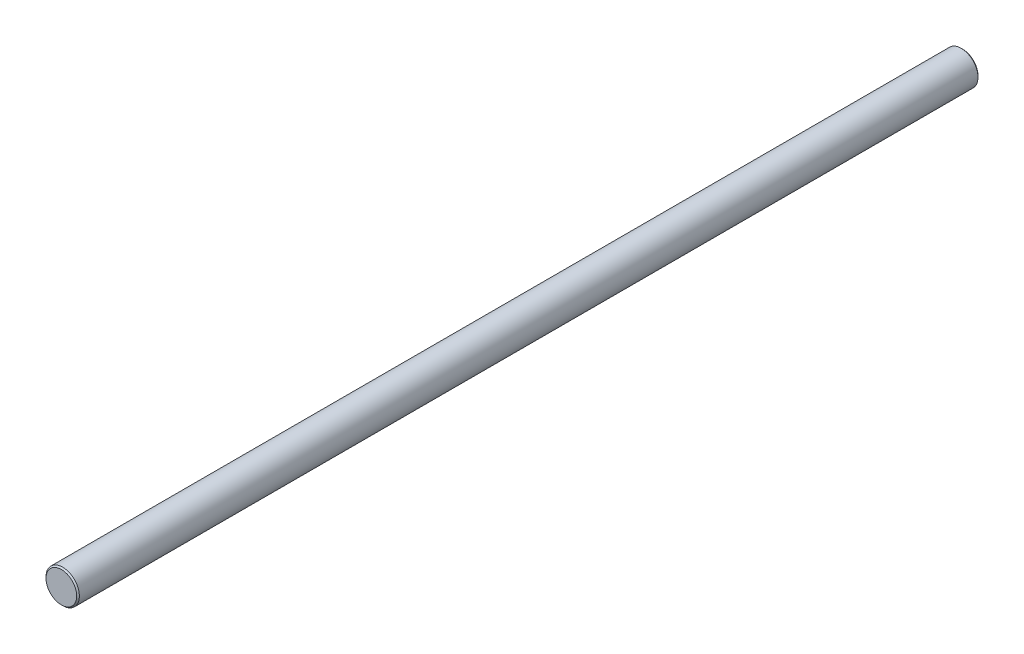
SolidWorks part; units mm, degrees
material "Vero PureWhite"
ref_plane "前视基准面" through (0, 0, 0) normal (0, 0, 1) x (1, 0, 0)
ref_plane "上视基准面" through (0, 0, 0) normal (0, 1, 0) x (1, 0, 0)
ref_plane "右视基准面" through (0, 0, 0) normal (1, 0, 0) x (0, 0, -1)
sketch "草图1" plane through (0, 0, 0) normal (0, 0, 1) x (1, 0, 0)
  circle A0 centre (0, 0) radius 2.5
  dimension "D1" = 5
extrude "凸台-拉伸1" add sketch "草图1" along normal blind 135
chamfer "倒角1" distance 0.2 angle 45 2 edges at (2.5, 0, 135) (2.5, 0, 0)
scale "缩放比例1" scale about origin uniform scaling yes scale factor 0.6
